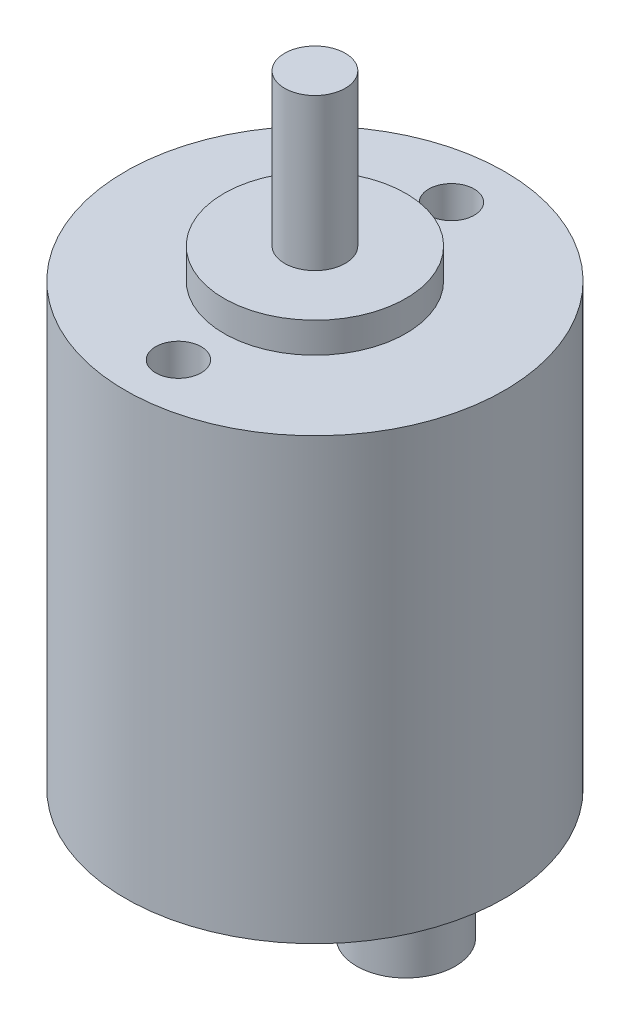
SolidWorks part; units mm, degrees
ref_plane "前视基准面" through (0, 0, 0) normal (0, 0, 1) x (1, 0, 0)
ref_plane "上视基准面" through (0, 0, 0) normal (0, 1, 0) x (1, 0, 0)
ref_plane "右视基准面" through (0, 0, 0) normal (1, 0, 0) x (0, 0, -1)
sketch "草图1" plane through (0, 0, 0) normal (0, 1, 0) x (0, 0, -1)
  circle A0 centre (0, 0) radius 12.5
  dimension "D1" = 25
extrude "凸台-拉伸3" add sketch "草图1" along normal blind 29
sketch "草图4" plane through (0, 29, 0) normal (0, 1, 0) x (0, 0, -1)
  circle A0 centre (0, 0) radius 6
  dimension "D1" = 12
extrude "凸台-拉伸4" add sketch "草图4" along normal blind 2
sketch "草图5" plane through (0, 31, 0) normal (0, 1, 0) x (0, 0, -1)
  circle A0 centre (0, 0) radius 2
  dimension "D1" = 4
extrude "凸台-拉伸5" add sketch "草图5" along normal blind 10
sketch "草图6" plane through (0, 41, 0) normal (0, 1, 0) x (0, 0, -1)
  circle A0 centre (0, 0) radius 9 construction
  circle A1 centre (-9, 0) radius 1.5
  circle A2 centre (9, 0) radius 1.5
  dimension "D1" = 18
  dimension "D2" = 3
  dimension "D3" = 3
extrude "切除-拉伸1" cut sketch "草图6" against normal blind 19
sketch "草图7" plane through (0, 0, 0) normal (0, -1, 0) x (0, 0, 1)
  line L0 (0, 0) -> (0, -6) construction
  circle A0 centre (0, -6) radius 3.25
  dimension "D2" = 6.5
  dimension "D1" = 6
extrude "凸台-拉伸6" add sketch "草图7" along normal blind 5.5
